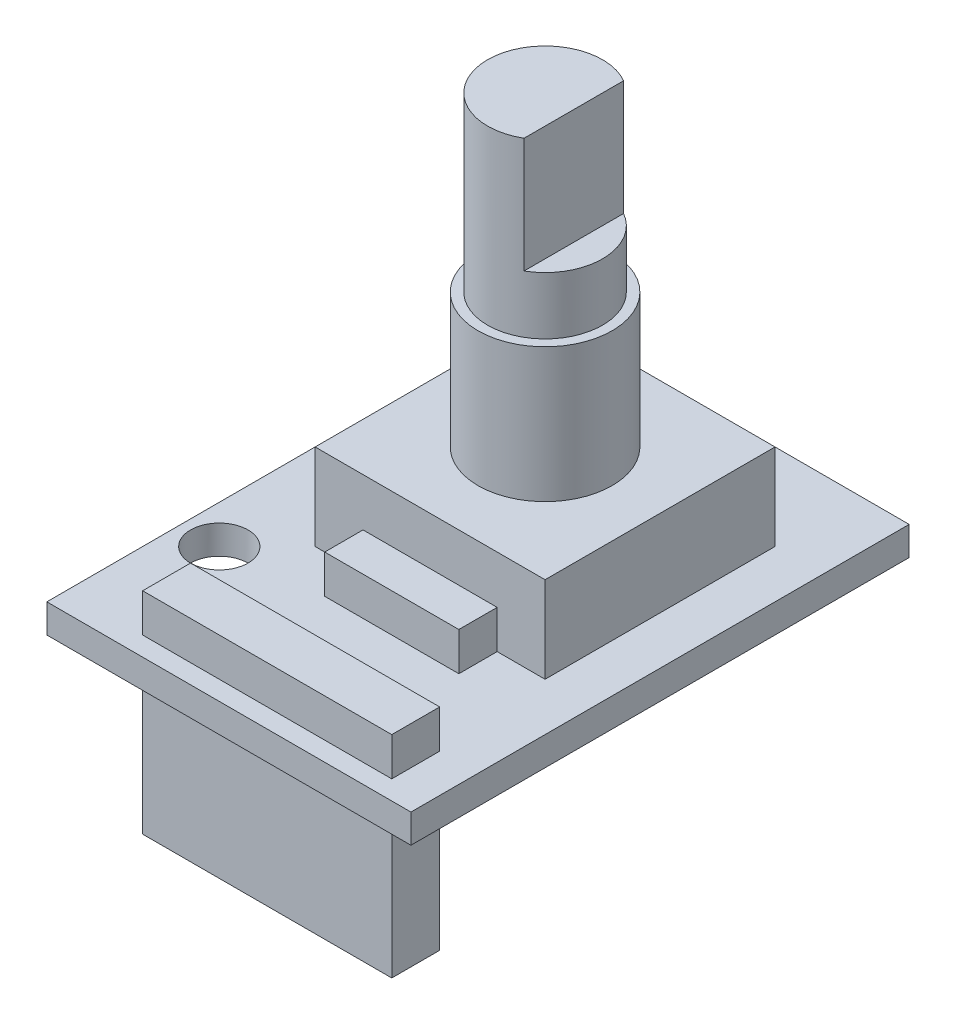
SolidWorks part; units mm, degrees
ref_plane "Piano frontale" through (0, 0, 0) normal (0, 0, 1) x (1, 0, 0)
ref_plane "Piano superiore" through (0, 0, 0) normal (0, 1, 0) x (1, 0, 0)
ref_plane "Piano destro" through (0, 0, 0) normal (1, 0, 0) x (0, 0, -1)
sketch "Schizzo1" plane through (0, 0, 0) normal (0, 1, 0) x (1, 0, 0)
  line L1 (-9.5, -13) -> (9.5, -13)
  line L2 (-9.5, -13) -> (-9.5, 13)
  line L3 (-9.5, 13) -> (9.5, 13)
  line L4 (9.5, -13) -> (9.5, 13)
  dimension "D1" = 19
  dimension "D2" = 26
  dimension "D3" = 13
  dimension "D4" = 9.5
extrude "Estrusione-Estrusione1" add sketch "Schizzo1" along normal blind 1.5
sketch "Schizzo2" plane through (0, 1.5, 0) normal (0, 1, 0) x (1, 0, 0)
  line L0 (9.5, -13) -> (9.5, 13) construction
  line L1 (-5, -3.5) -> (7, -3.5)
  line L2 (-5, -3.5) -> (-5, 8.5)
  line L3 (-5, 8.5) -> (7, 8.5)
  line L4 (7, -3.5) -> (7, 8.5)
  line L5 (9.5, 13) -> (-9.5, 13) construction
  dimension "D1" = 12
  dimension "D2" = 12
  dimension "D3" = 2.5
  dimension "D4" = 4.5
extrude "Estrusione-Estrusione2" add sketch "Schizzo2" along normal blind 4.5
sketch "Schizzo4" plane through (0, 6, 0) normal (0, 1, 0) x (1, 0, 0)
  line L1 (7, 8.5) -> (-5, 8.5) construction
  line L3 (7, -3.5) -> (7, 8.5) construction
  circle A0 centre (1, 2.5) radius 3.5
  dimension "D2" = 6
  dimension "D3" = 7
  dimension "D1" = 6
extrude "Estrusione-Estrusione3" add sketch "Schizzo4" along normal blind 7
sketch "Schizzo5" plane through (0, 13, 0) normal (0, 1, 0) x (1, 0, 0)
  circle A0 centre (1, 2.5) radius 3
  circle A1 centre (1, 2.5) radius 3.5 construction
  dimension "D1" = 6
extrude "Estrusione-Estrusione4" add sketch "Schizzo5" along normal blind 9
sketch "Schizzo6" plane through (0, 22, 0) normal (0, 1, 0) x (1, 0, 0)
  line L0 (2.5, 5.0981) -> (2.5, -0.0981)
  circle A0 centre (1, 2.5) radius 3
  circle M3 centre (1, 2.5) radius 3
  dimension "D1" = 6
  dimension "D2" = 1.5
extrude "Taglio-Estrusione1" cut sketch "Schizzo6" against normal blind 6 contours L0 M3
sketch "Schizzo7" plane through (0, 1.5, 0) normal (0, 1, 0) x (1, 0, 0)
  line L0 (-9.5, 13) -> (-9.5, -13) construction
  line L1 (9.5, 13) -> (-9.5, 13) construction
  line L2 (-9.5, -13) -> (9.5, -13) construction
  circle A0 centre (-7.5, 7.5) radius 1.5
  circle A1 centre (-7.5, -6) radius 1.5
  dimension "D1" = 3
  dimension "D2" = 3
  dimension "D3" = 2
  dimension "D4" = 2
  dimension "D5" = 5.5
  dimension "D6" = 7
extrude "Taglio-Estrusione2" cut sketch "Schizzo7" against normal blind 6
sketch "Schizzo8" plane through (0, 1.5, 0) normal (0, 1, 0) x (1, 0, 0)
  line L0 (9.5, -13) -> (9.5, 13) construction
  line L1 (-5.5, -12) -> (7.5, -12)
  line L2 (-5.5, -12) -> (-5.5, -9.5)
  line L3 (-5.5, -9.5) -> (7.5, -9.5)
  line L4 (7.5, -12) -> (7.5, -9.5)
  line L5 (-9.5, -13) -> (9.5, -13) construction
  dimension "D1" = 2.5
  dimension "D2" = 13
  dimension "D3" = 2
  dimension "D4" = 1
extrude "Estrusione-Estrusione5" add sketch "Schizzo8" along normal blind 2 and the other way blind 9
sketch "Schizzo9" plane through (0, 0, 0) normal (0, -1, 0) x (1, 0, 0)
  line L1 (-3, 6.5) -> (6.5, 6.5)
  line L2 (-3, 6.5) -> (-3, -12)
  line L3 (-3, -12) -> (6.5, -12)
  line L4 (6.5, 6.5) -> (6.5, -12)
  line L5 (9.5, 13) -> (9.5, -13) construction
  line L6 (9.5, -13) -> (-9.5, -13) construction
  line L7 (-5.5, 9.5) -> (7.5, 9.5) construction
  circle A0 centre (-7.5, 6) radius 1.5 construction
  dimension "D1" = 4.5
  dimension "D2" = 3
  dimension "D3" = 1
  dimension "D4" = 3
extrude "Estrusione-Estrusione6" add sketch "Schizzo9" along normal blind 1.5
sketch "Schizzo10" plane through (0, 1.5, 0) normal (0, 1, 0) x (1, 0, 0)
  line L0 (7, 8.5) -> (-5, 8.5) construction
  line L1 (-2.5, 8.5) -> (4.5, 8.5)
  line L2 (-2.5, 8.5) -> (-2.5, 10.5)
  line L3 (-2.5, 10.5) -> (4.5, 10.5)
  line L4 (4.5, 8.5) -> (4.5, 10.5)
  line L5 (-5, -3.5) -> (7, -3.5) construction
  line L6 (-2.5, -3.5) -> (4.5, -3.5)
  line L7 (-2.5, -3.5) -> (-2.5, -5.5)
  line L8 (-2.5, -5.5) -> (4.5, -5.5)
  line L9 (4.5, -3.5) -> (4.5, -5.5)
  line L10 (-5, 8.5) -> (-5, -3.5) construction
  dimension "D1" = 7
  dimension "D2" = 2
  dimension "D3" = 2
  dimension "D4" = 7
  dimension "D5" = 2.5
  dimension "D6" = 2.5
extrude "Estrusione-Estrusione7" add sketch "Schizzo10" along normal blind 2
